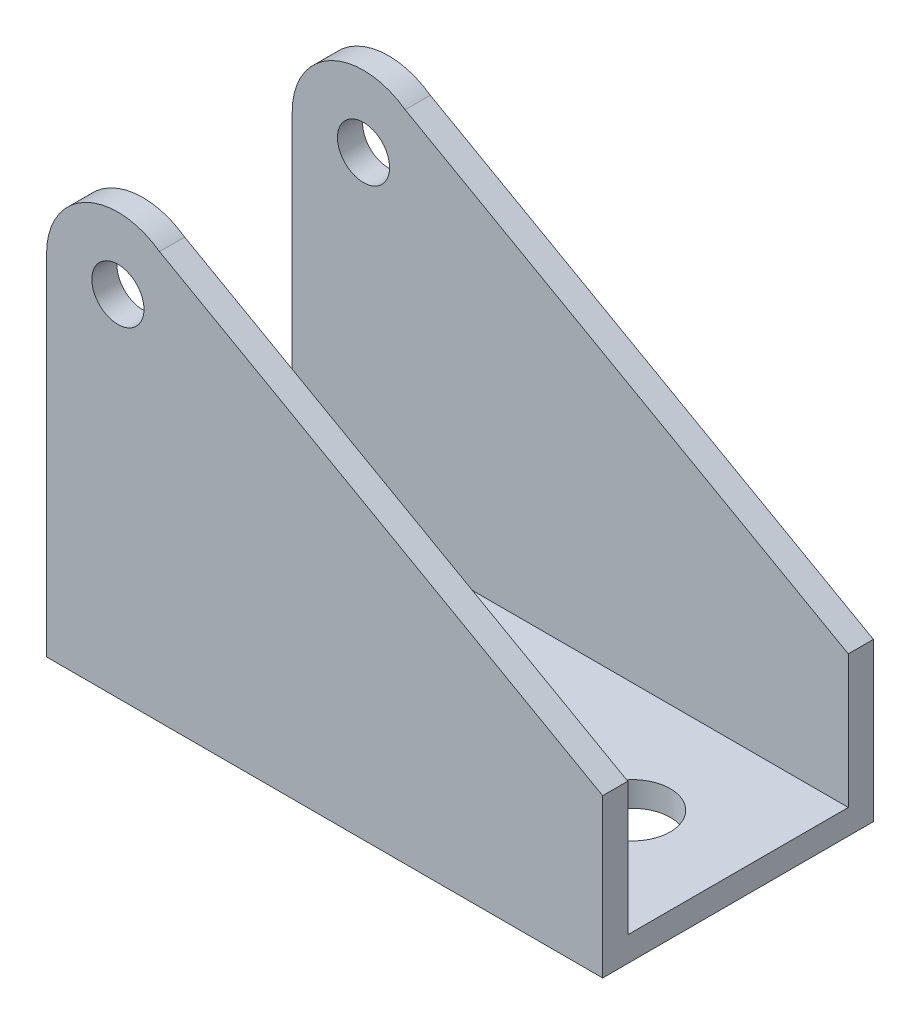
SolidWorks part; units mm, degrees
material "AISI 304"
ref_plane "前视基准面" through (0, 0, 0) normal (0, 0, 1) x (1, 0, 0)
ref_plane "上视基准面" through (0, 0, 0) normal (0, 1, 0) x (1, 0, 0)
ref_plane "右视基准面" through (0, 0, 0) normal (1, 0, 0) x (0, 0, -1)
other "Configuration Table"
sketch "草图1" plane through (0, 0, 0) normal (0, 0, 1) x (1, 0, 0)
  line L0 (-34.5094, -1.8049) -> (-34.5094, -38.3049)
  line L1 (-34.5094, -38.3049) -> (23.5306, -38.3049)
  line L2 (23.5306, -38.3049) -> (23.5306, -21.8249)
  line L4 (-22.7212, 4.2323) -> (23.5306, -21.8249)
  circle A2 centre (-27.0694, -1.8049) radius 2.72
  arc A3 (-34.5094, -1.8049) -> (-22.7212, 4.2323) centre (-27.0694, -1.8049) cw
  point P7 (-6.7235, 63.2565)
  dimension "D1" = 16.48
  dimension "D2" = 36.5
  dimension "D3" = 58.04
extrude "凸台-拉伸4" add sketch "草图1" along normal blind 28.26
ref_plane "基准面1" through (0, 0, 14.13) normal (0, 0, 1) x (1, 0, 0)
sketch "草图2" plane through (0, 0, 14.13) normal (0, 0, 1) x (1, 0, 0)
  line L8 (-35.9563, -0.3398) -> (-37.6969, -35.7076)
  line L9 (-37.6969, -35.7076) -> (23.9354, -35.7076)
  line L10 (23.9354, -35.7076) -> (23.9354, -19.5799)
  line L11 (-18.7501, 5.1878) -> (23.9354, -19.5799)
  circle A5 centre (-27.2115, 1.9829) radius 2.72
  arc A6 (-35.9563, -0.3398) -> (-18.7501, 5.1878) centre (-27.2115, 1.9829) cw
extrude "切除-拉伸1" cut sketch "草图2" against normal mid plane 23.02 contours L8 L9 L10 L11 A6
sketch "草图3" plane through (0, -35.7076, 0) normal (0, 1, 0) x (1, 0, 0)
  line L0 (23.5306, -14.13) -> (16.4506, -14.13)
  line L1 (23.5306, -2.62) -> (23.5306, -25.64) construction
  line L2 (-34.5094, 0) -> (-34.5094, -8.04)
  line L3 (-34.5094, -25.64) -> (-34.5094, -2.62) construction
  line L6 (-26.3194, -10.04) -> (-34.5094, -10.04)
  line L7 (-26.3194, -18.22) -> (-34.5094, -18.22)
  circle A0 centre (12.5306, -14.13) radius 3.92
  arc A1 (-26.3194, -18.22) -> (-26.3194, -10.04) centre (-26.3194, -14.13) ccw
  line M6 (-34.5094, -2.62) -> (-34.5094, -25.64)
  dimension "D1" = 7.84
  dimension "D5" = 8.18
  dimension "D2" = 8.04
extrude "切除-拉伸2" cut sketch "草图3" against normal blind 10 contours A0 | L7 A1 L6 M6
